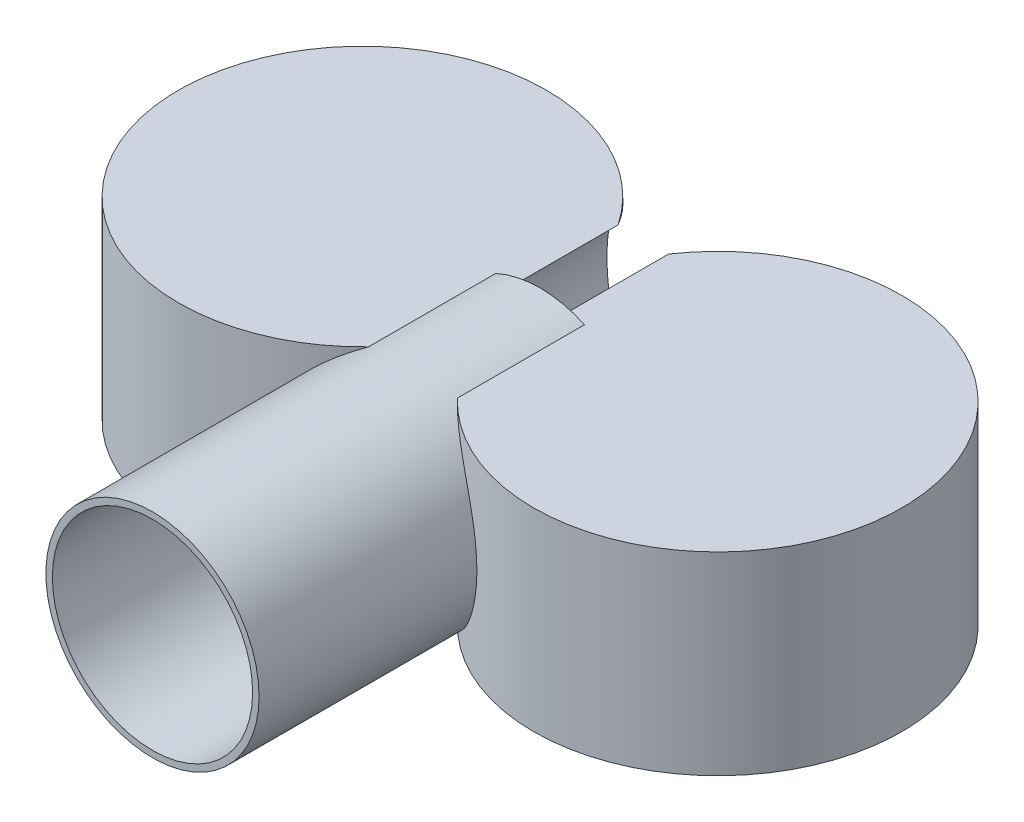
SolidWorks part; units mm, degrees
ref_plane "Front Plane" through (0, 0, 0) normal (0, 0, 1) x (1, 0, 0)
ref_plane "Top Plane" through (0, 0, 0) normal (0, 1, 0) x (1, 0, 0)
ref_plane "Right Plane" through (0, 0, 0) normal (1, 0, 0) x (0, 0, -1)
sketch "Sketch1" plane through (0, 0, 0) normal (0, 1, 0) x (1, 0, 0)
  arc A0 (-15.0193, 7.4833) -> (-15.0193, -7.4833) centre (-42.5193, 0) ccw
  arc A1 (-15.0193, -7.4833) -> (-15.0193, 7.4833) centre (12.4807, 0) ccw
  dimension "D1" = 57
  dimension "D2" = 55
extrude "Boss-Extrude1" add sketch "Sketch1" along normal blind 30
sketch "Sketch2" plane through (0, 0, 0) normal (0, 0, 1) x (1, 0, 0)
  line L0 (-15.0193, 30) -> (-15.0193, 0) construction
  circle A0 centre (-15.0193, 15) radius 16.5
  dimension "D1" = 33
extrude "Boss-Extrude2" add sketch "Sketch2" along normal blind 60
sketch "Sketch3" plane through (0, 0, 60) normal (0, 0, 1) x (1, 0, 0)
  circle A0 centre (-15.0193, 15) radius 15.5
  dimension "D1" = 31
extrude "Cut-Extrude1" cut sketch "Sketch3" against normal through all
